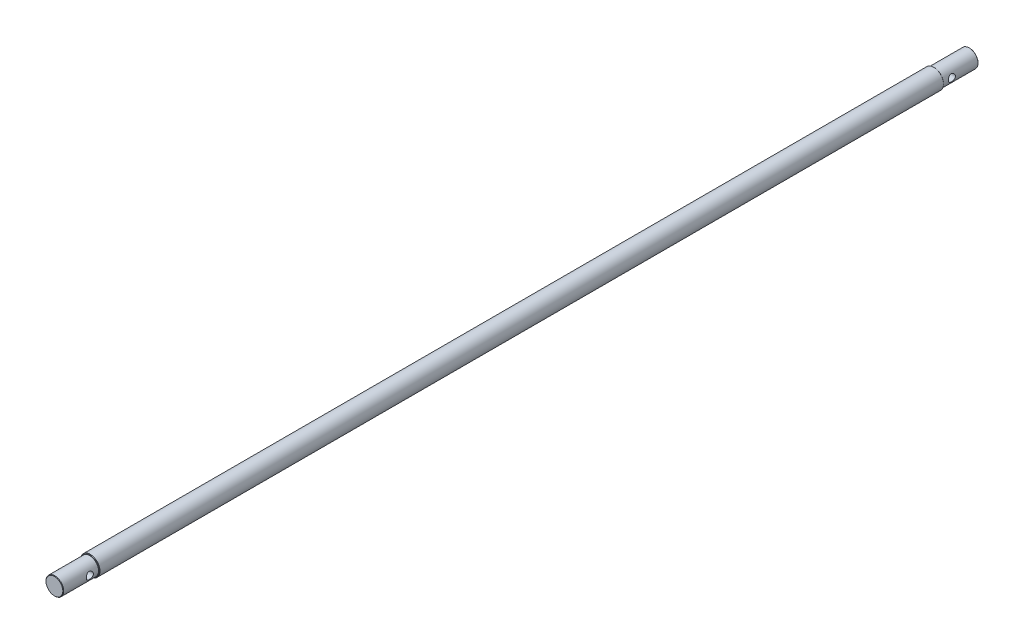
SolidWorks part; units mm, degrees
ref_plane "Спереди" through (0, 0, 0) normal (0, 0, 1) x (1, 0, 0)
ref_plane "Сверху" through (0, 0, 0) normal (0, 1, 0) x (1, 0, 0)
ref_plane "Справа" through (0, 0, 0) normal (1, 0, 0) x (0, 0, -1)
sketch "Эскиз1" plane through (0, 0, 0) normal (1, 0, 0) x (0, 0, -1)
  line L0 (0, 0) -> (0, 10)
  line L1 (0, 10) -> (40, 10)
  line L2 (40, 10) -> (40, 11)
  line L3 (40, 11) -> (994, 11)
  line L4 (994, 11) -> (994, 10)
  line L5 (994, 10) -> (1034, 10)
  line L6 (1034, 10) -> (1034, 0)
  line L7 (0, 0) -> (1034, 0)
  dimension "D1" = 10
  dimension "D2" = 10
  dimension "D3" = 1
  dimension "D4" = 954
  dimension "D5" = 40
  dimension "D6" = 40
revolve "Повернуть1" add sketch "Эскиз1" angle 360 about L7
ref_plane "Плоскость1" through (-10, 0, 0) normal (-1, 0, 0) x (0, 0, 1)
ref_plane "Плоскость2" through (-10, 0, 0) normal (-1, 0, 0) x (0, 0, 1)
sketch "Эскиз2" plane through (-10, 0, 0) normal (-1, 0, 0) x (0, 0, 1)
  line L0 (-40, -10) -> (0, -10) construction
  line L1 (-40, -10) -> (-40, 10) construction
  circle A0 centre (-30, 0) radius 4
  dimension "D1" = 8
  dimension "D2" = 10
  dimension "D3" = 10
extrude "Вырез-Вытянуть1" cut sketch "Эскиз2" against normal through all
sketch "Эскиз3" plane through (-10, 0, 0) normal (-1, 0, 0) x (0, 0, 1)
  line L0 (-1034, -10) -> (-994, -10) construction
  line L1 (-994, 10) -> (-994, -10) construction
  circle A0 centre (-1004, 0) radius 4
  dimension "D1" = 8
  dimension "D2" = 10
  dimension "D3" = 10
extrude "Вырез-Вытянуть2" cut sketch "Эскиз3" against normal through all contours A0
fillet "Скругление1" radius 0.2 2 edges at (10, 0, -40) (10, 0, -994)
chamfer "Фаска1" distance 0.5 angle 45 4 edges at (11, 0, -994) (10, 0, -1034) (10, 0, 0) (11, 0, -40)
